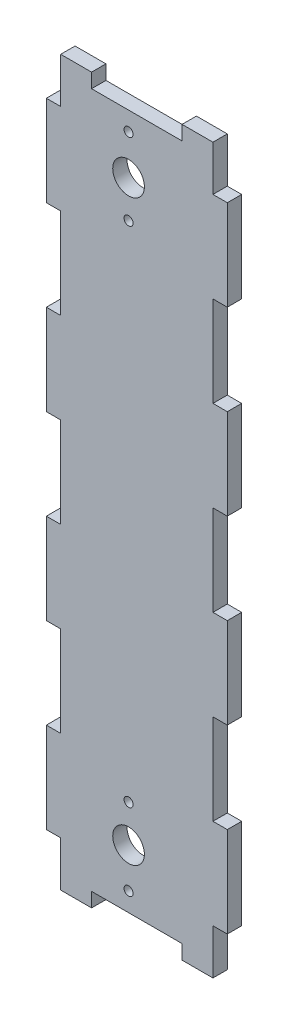
SolidWorks part; units mm, degrees
ref_plane "Front Plane" through (0, 0, 0) normal (0, 0, 1) x (1, 0, 0)
ref_plane "Top Plane" through (0, 0, 0) normal (0, 1, 0) x (1, 0, 0)
ref_plane "Right Plane" through (0, 0, 0) normal (1, 0, 0) x (0, 0, -1)
sketch "Sketch1" plane through (0, 0, -55.9568) normal (0, 0, -1) x (-1, 0, 0)
  line L1 (-5.3765, 185.3163) -> (-45.3765, 185.3163)
  line L2 (-5.3765, 185.3163) -> (-5.3765, 25.3163)
  line L3 (-5.3765, 25.3163) -> (-45.3765, 25.3163)
  line L4 (-45.3765, 185.3163) -> (-45.3765, 25.3163)
  dimension "D1" = 160
  dimension "D2" = 40
extrude "Boss-Extrude1" add sketch "Sketch1" against normal blind 3.175
sketch "Sketch2" plane through (0, 0, -55.9568) normal (0, 0, -1) x (-1, 0, 0)
  line L0 (-5.3765, 185.3163) -> (-5.3765, 175.3163) construction
  line L1 (-5.3765, 175.3163) -> (-8.5515, 175.3163) construction
  line L2 (-8.5515, 175.3163) -> (-8.5515, 185.3163) construction
  line L3 (-8.5515, 185.3163) -> (-5.3765, 185.3163) construction
  line L4 (-8.5515, 135.3163) -> (-8.5515, 155.3163) construction
  line L5 (-8.5515, 155.3163) -> (-5.3765, 155.3163) construction
  line L6 (-5.3765, 155.3163) -> (-5.3765, 135.3163) construction
  line L7 (-5.3765, 135.3163) -> (-8.5515, 135.3163) construction
  line L8 (-8.5515, 95.3163) -> (-8.5515, 115.3163) construction
  line L9 (-8.5515, 115.3163) -> (-5.3765, 115.3163) construction
  line L10 (-5.3765, 115.3163) -> (-5.3765, 95.3163) construction
  line L11 (-5.3765, 95.3163) -> (-8.5515, 95.3163) construction
  line L12 (-8.5515, 55.3163) -> (-8.5515, 75.3163) construction
  line L13 (-8.5515, 75.3163) -> (-5.3765, 75.3163) construction
  line L14 (-5.3765, 75.3163) -> (-5.3765, 55.3163) construction
  line L15 (-5.3765, 55.3163) -> (-8.5515, 55.3163) construction
  line L16 (-8.5515, 25.3163) -> (-8.5515, 35.3163) construction
  line L17 (-8.5515, 35.3163) -> (-5.3765, 35.3163) construction
  line L18 (-5.3765, 35.3163) -> (-5.3765, 25.3163) construction
  line L19 (-5.3765, 25.3163) -> (-8.5515, 25.3163) construction
  line L20 (-5.3765, 185.3163) -> (-5.3765, 175.3163)
  line L21 (-5.3765, 175.3163) -> (-8.5515, 175.3163)
  line L22 (-8.5515, 175.3163) -> (-8.5515, 185.3163)
  line L23 (-8.5515, 185.3163) -> (-5.3765, 185.3163)
  line L24 (-8.5515, 135.3163) -> (-8.5515, 155.3163)
  line L25 (-8.5515, 155.3163) -> (-5.3765, 155.3163)
  line L26 (-5.3765, 155.3163) -> (-5.3765, 135.3163)
  line L27 (-5.3765, 135.3163) -> (-8.5515, 135.3163)
  line L28 (-8.5515, 95.3163) -> (-8.5515, 115.3163)
  line L29 (-8.5515, 115.3163) -> (-5.3765, 115.3163)
  line L30 (-5.3765, 115.3163) -> (-5.3765, 95.3163)
  line L31 (-5.3765, 95.3163) -> (-8.5515, 95.3163)
  line L32 (-8.5515, 55.3163) -> (-8.5515, 75.3163)
  line L33 (-8.5515, 75.3163) -> (-5.3765, 75.3163)
  line L34 (-5.3765, 75.3163) -> (-5.3765, 55.3163)
  line L35 (-5.3765, 55.3163) -> (-8.5515, 55.3163)
  line L36 (-8.5515, 25.3163) -> (-8.5515, 35.3163)
  line L37 (-8.5515, 35.3163) -> (-5.3765, 35.3163)
  line L38 (-5.3765, 35.3163) -> (-5.3765, 25.3163)
  line L39 (-5.3765, 25.3163) -> (-8.5515, 25.3163)
extrude "Cut-Extrude1" cut sketch "Sketch2" against normal up to surface (3.175 mm away) up to face at (25.3765, 105.3163, -52.7818)
sketch "Sketch3" plane through (0, 0, -55.9568) normal (0, 0, -1) x (-1, 0, 0)
  circle A0 centre (-23.5515, 32.6664) radius 1 construction
  circle A1 centre (-23.5515, 49.6664) radius 1 construction
  circle A2 centre (-23.5515, 32.6664) radius 1
  circle A3 centre (-23.5515, 49.6664) radius 1
extrude "Cut-Extrude2" cut sketch "Sketch3" against normal up to surface (3.175 mm away) up to face at (10.964, 105.3163, -52.7818)
ref_plane "Plane1" through (25.3765, 0, 0) normal (-1, 0, 0) x (0, 0, 1)
mirror "Mirror1" about plane through (25.3765, 0, 0) normal (-1, 0, 0) of "Cut-Extrude1"
sketch "Sketch4" plane through (0, 0, -55.9568) normal (0, 0, -1) x (-1, 0, 0)
  line L0 (-42.2015, 25.3163) -> (-8.5515, 25.3163) construction
  line L1 (-15.3765, 25.3163) -> (-35.3765, 25.3163)
  line L2 (-15.3765, 25.3163) -> (-15.3765, 28.4913)
  line L3 (-15.3765, 28.4913) -> (-35.3765, 28.4913)
  line L4 (-35.3765, 25.3163) -> (-35.3765, 28.4913)
  line L6 (-8.5515, 185.3163) -> (-42.2015, 185.3163) construction
  line L7 (-15.3765, 185.3163) -> (-35.3765, 185.3163)
  line L8 (-15.3765, 185.3163) -> (-15.3765, 182.1413)
  line L9 (-15.3765, 182.1413) -> (-35.3765, 182.1413)
  line L10 (-35.3765, 185.3163) -> (-35.3765, 182.1413)
  dimension "D1" = 20
  dimension "D2" = 3.175
  dimension "D3" = 6.825
  dimension "D4" = 3.175
  dimension "D5" = 20
  dimension "D6" = 6.825
extrude "Cut-Extrude3" cut sketch "Sketch4" against normal up to surface (3.175 mm away) up to face at (24.5515, 32.6664, -52.7818)
sketch "Sketch5" plane through (0, 0, -55.9568) normal (0, 0, -1) x (-1, 0, 0)
  circle A0 centre (-23.5515, 41.4252) radius 3.5 construction
  circle A1 centre (-23.5515, 41.4252) radius 3.5
extrude "Cut-Extrude4" cut sketch "Sketch5" against normal blind 3.175
ref_plane "Plane2" through (0, 105.3163, 0) normal (0, -1, 0) x (-1, 0, 0)
mirror "Mirror2" about plane through (0, 105.3163, 0) normal (0, -1, 0) of "Cut-Extrude4", "Cut-Extrude2"
